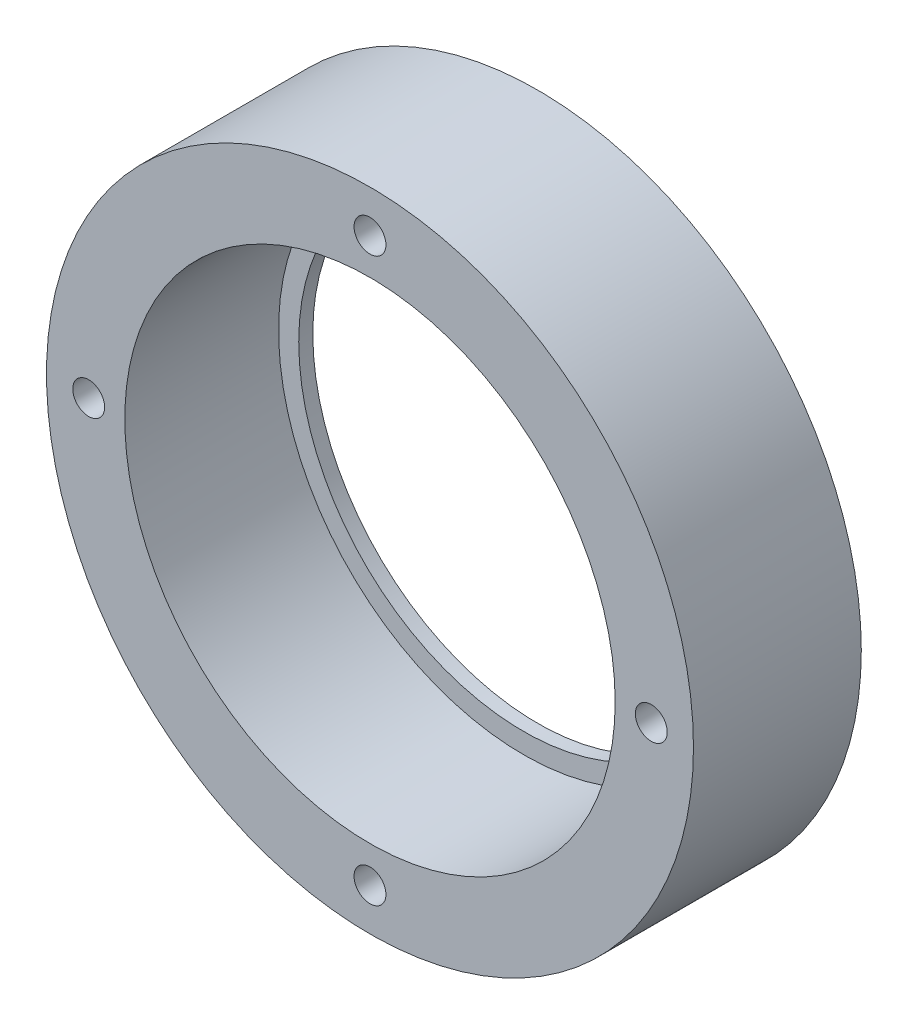
SolidWorks part; units mm, degrees
ref_plane "Front Plane" through (0, 0, 0) normal (0, 0, 1) x (1, 0, 0)
ref_plane "Top Plane" through (0, 0, 0) normal (0, 1, 0) x (1, 0, 0)
ref_plane "Right Plane" through (0, 0, 0) normal (1, 0, 0) x (0, 0, -1)
sketch "Sketch1" plane through (0, 0, 0) normal (0, 0, 1) x (1, 0, 0)
  circle A0 centre (0, 0) radius 34.5
  circle A1 centre (0, 0) radius 24
  dimension "D1" = 69
  dimension "D2" = 48
extrude "Boss-Extrude1" add sketch "Sketch1" along normal blind 1.5
sketch "Sketch3" plane through (0, 0, 1.5) normal (0, 0, 1) x (1, 0, 0)
  circle A0 centre (0, 0) radius 26.15
  circle A1 centre (0, 0) radius 34.5
  dimension "D1" = 52.3
  dimension "D2" = 69
extrude "Boss-Extrude2" add sketch "Sketch3" along normal blind 16.4
sketch "Sketch4" plane through (0, 0, 17.9) normal (0, 0, 1) x (1, 0, 0)
  circle A0 centre (0, 30) radius 1.7
  circle A1 centre (30, 0) radius 1.7
  circle A2 centre (0, -30) radius 1.7
  circle A3 centre (-30, 0) radius 1.7
  dimension "D1" = 3.4
  dimension "D2" = 3.4
  dimension "D3" = 3.4
  dimension "D4" = 3.4
  dimension "D5" = 30
  dimension "D6" = 30
  dimension "D7" = 30
  dimension "D8" = 30
extrude "Cut-Extrude1" cut sketch "Sketch4" against normal through all
chamfer "Chamfer1" distance 0.4 angle 45 4 edges at (1.7, -30, 0) (31.7, 0, 0) (-28.3, 0, 0) (1.7, 30, 0)
